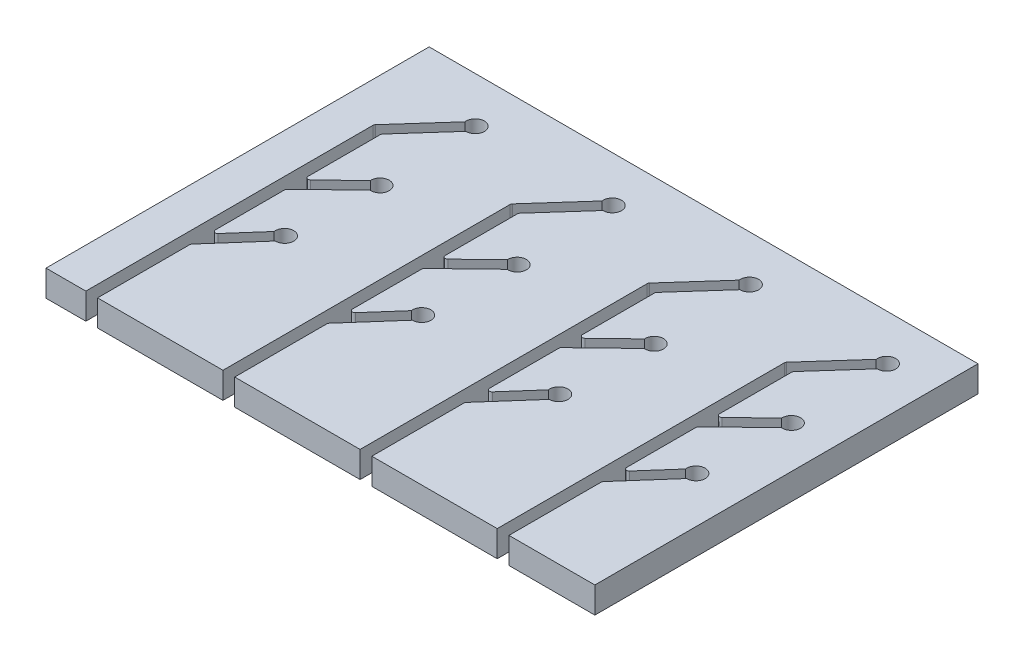
SolidWorks part; units mm, degrees
ref_plane "Front Plane" through (0, 0, 0) normal (0, 0, 1) x (1, 0, 0)
ref_plane "Top Plane" through (0, 0, 0) normal (0, 1, 0) x (1, 0, 0)
ref_plane "Right Plane" through (0, 0, 0) normal (1, 0, 0) x (0, 0, -1)
ref_plane "Plane1" through (0, 10, 0) normal (0, 1, 0) x (1, 0, 0)
sketch "Sketch1" plane through (0, 10, 0) normal (0, 1, 0) x (1, 0, 0)
  line L0 (-60.6438, -106.3471) -> (-60.6438, -33.3849) construction
  line L1 (-95.6438, 187.0307) -> (324.624, 187.0307)
  line L2 (-95.6438, 187.0307) -> (-95.6438, -106.3471)
  line L3 (-95.6438, -106.3471) -> (324.624, -106.3471)
  line L4 (324.624, 187.0307) -> (324.624, -106.3471)
  line L5 (-60.6438, -33.3849) -> (-25.6438, 6.3439) construction
  line L6 (-60.6438, -33.3849) -> (-60.6438, 39.5772) construction
  line L7 (-60.6438, 39.5772) -> (-22.544, 76.3439) construction
  line L8 (-60.6438, 39.5772) -> (-60.6438, 112.5394) construction
  line L9 (-60.6438, 112.5394) -> (-25.376, 152.0307) construction
  line L10 (-25.6438, 6.3439) -> (-60.6438, 6.3439) construction
  line L11 (-56.1438, 54.8828) -> (-56.1438, 110.0594)
  line L12 (-55.6355, 111.3916) -> (-22.0196, 149.0333)
  line L13 (-55.5326, 38.256) -> (-19.4192, 73.1058)
  line L14 (-56.1438, -16.1737) -> (-56.1438, 36.8168)
  line L15 (-55.6445, -34.5176) -> (-22.2672, 3.3693)
  line L16 (-56.1438, -106.3471) -> (-56.1438, -35.8397)
  line L17 (-65.1438, 39.5772) -> (-65.1438, 113.4932)
  line L18 (-64.6355, 114.8254) -> (-28.7324, 155.0282)
  line L19 (-52.7549, 53.4436) -> (-25.6688, 79.5821)
  line L20 (-65.1438, -33.3849) -> (-65.1438, 39.5772)
  line L21 (-52.6431, -17.4958) -> (-29.0203, 9.3186)
  line L22 (-65.1438, -106.3471) -> (-65.1438, -33.3849)
  line L35 (49.3645, 111.3916) -> (82.9804, 149.0333)
  line L36 (40.3645, 114.8254) -> (76.2676, 155.0282)
  line L37 (48.8562, 54.8828) -> (48.8562, 110.0594)
  line L38 (39.8562, 39.5772) -> (39.8562, 113.4932)
  line L39 (52.2451, 53.4436) -> (79.3312, 79.5821)
  line L40 (49.4674, 38.256) -> (85.5808, 73.1058)
  line L41 (48.8562, -16.1737) -> (48.8562, 36.8168)
  line L54 (39.8562, -33.3849) -> (39.8562, 39.5772)
  line L55 (49.3555, -34.5176) -> (82.7328, 3.3693)
  line L56 (52.3569, -17.4958) -> (75.9797, 9.3186)
  line L57 (48.8562, -106.3471) -> (48.8562, -35.8397)
  line L58 (39.8562, -106.3471) -> (39.8562, -33.3849)
  line L59 (154.3645, 111.3916) -> (187.9804, 149.0333)
  line L60 (145.3645, 114.8254) -> (181.2676, 155.0282)
  line L73 (153.8562, 54.8828) -> (153.8562, 110.0594)
  line L74 (144.8562, 39.5772) -> (144.8562, 113.4932)
  line L75 (157.2451, 53.4436) -> (184.3312, 79.5821)
  line L76 (154.4674, 38.256) -> (190.5808, 73.1058)
  line L77 (153.8562, -16.1737) -> (153.8562, 36.8168)
  line L78 (144.8562, -33.3849) -> (144.8562, 39.5772)
  line L79 (154.3555, -34.5176) -> (187.7328, 3.3693)
  line L80 (-57.5189, 36.3391) -> (-19.4192, 73.1058) construction
  line L81 (-56.1438, -33.3849) -> (-56.1438, 39.5772) construction
  line L82 (-56.1438, -106.3471) -> (-56.1438, -33.3849) construction
  line L83 (-57.2672, -36.3596) -> (-22.2672, 3.3693) construction
  line L84 (-64.0203, -30.4102) -> (-29.0203, 9.3186) construction
  line L85 (-63.7686, 42.8153) -> (-25.6688, 79.5821) construction
  line L86 (-56.1438, 39.5772) -> (-56.1438, 110.8225) construction
  line L87 (-65.1438, 39.5772) -> (-65.1438, 114.2562) construction
  line L88 (-65.1438, 114.2562) -> (-28.7324, 155.0282) construction
  line L89 (-56.1438, 110.8225) -> (-22.0196, 149.0333) construction
  line L90 (157.3569, -17.4958) -> (180.9797, 9.3186)
  line L91 (153.8562, -106.3471) -> (153.8562, -35.8397)
  line L92 (144.8562, -106.3471) -> (144.8562, -33.3849)
  line L93 (259.3645, 111.3916) -> (292.9804, 149.0333)
  line L94 (250.3645, 114.8254) -> (286.2676, 155.0282)
  line L95 (258.8562, 54.8828) -> (258.8562, 110.0594)
  line L96 (249.8562, 39.5772) -> (249.8562, 113.4932)
  line L97 (262.2451, 53.4436) -> (289.3312, 79.5821)
  line L98 (259.4674, 38.256) -> (295.5808, 73.1058)
  line L99 (258.8562, -16.1737) -> (258.8562, 36.8168)
  line L100 (249.8562, -33.3849) -> (249.8562, 39.5772)
  line L101 (259.3555, -34.5176) -> (292.7328, 3.3693)
  line L102 (262.3569, -17.4958) -> (285.9797, 9.3186)
  line L103 (258.8562, -106.3471) -> (258.8562, -35.8397)
  line L104 (249.8562, -106.3471) -> (249.8562, -33.3849)
  arc A0 (-56.1438, 39.5772) -> (-65.1438, 39.5772) centre (-60.6438, 39.5772) cw
  arc A1 (-22.0196, 149.0333) -> (-28.7324, 155.0282) centre (-25.376, 152.0307) ccw
  arc A2 (-57.5189, 36.3391) -> (-63.7686, 42.8153) centre (-60.6438, 39.5772) cw
  arc A3 (-19.4192, 73.1058) -> (-25.6688, 79.5821) centre (-22.544, 76.3439) ccw
  arc A4 (-56.1438, -33.3849) -> (-65.1438, -33.3849) centre (-60.6438, -33.3849) cw
  arc A5 (-56.1438, 39.5772) -> (-65.1438, 39.5772) centre (-60.6438, 39.5772) ccw
  arc A6 (-57.2672, -36.3596) -> (-64.0203, -30.4102) centre (-60.6438, -33.3849) cw
  arc A7 (-22.2672, 3.3693) -> (-29.0203, 9.3186) centre (-25.6438, 6.3439) ccw
  arc A8 (-56.1438, -106.3471) -> (-65.1438, -106.3471) centre (-60.6438, -106.3471) cw
  arc A9 (-56.1438, -33.3849) -> (-65.1438, -33.3849) centre (-60.6438, -33.3849) ccw
  circle A10 centre (-25.376, 152.0307) radius 7
  circle A11 centre (-22.544, 76.3439) radius 7
  circle A12 centre (-25.6438, 6.3439) radius 7
  arc A52 (-55.5326, 38.256) -> (-56.1438, 36.8168) centre (-54.1438, 36.8168) ccw
  arc A53 (-56.1438, -35.8397) -> (-55.6445, -34.5176) centre (-54.1438, -35.8397) cw
  arc A54 (-56.1438, -16.1737) -> (-52.6431, -17.4958) centre (-54.1438, -16.1737) ccw
  arc A55 (-52.7549, 53.4436) -> (-56.1438, 54.8828) centre (-54.1438, 54.8828) cw
  arc A56 (-65.1438, 113.4932) -> (-64.6355, 114.8254) centre (-63.1438, 113.4932) cw
  arc A57 (-56.1438, 110.0594) -> (-55.6355, 111.3916) centre (-54.1438, 110.0594) cw
  circle A58 centre (79.624, 152.0307) radius 7
  arc A59 (48.8562, 110.0594) -> (49.3645, 111.3916) centre (50.8562, 110.0594) cw
  arc A60 (39.8562, 113.4932) -> (40.3645, 114.8254) centre (41.8562, 113.4932) cw
  arc A61 (52.2451, 53.4436) -> (48.8562, 54.8828) centre (50.8562, 54.8828) cw
  circle A62 centre (82.456, 76.3439) radius 7
  arc A63 (49.4674, 38.256) -> (48.8562, 36.8168) centre (50.8562, 36.8168) ccw
  circle A64 centre (79.3562, 6.3439) radius 7
  arc A65 (48.8562, -16.1737) -> (52.3569, -17.4958) centre (50.8562, -16.1737) ccw
  arc A66 (48.8562, -35.8397) -> (49.3555, -34.5176) centre (50.8562, -35.8397) cw
  circle A67 centre (184.624, 152.0307) radius 7
  arc A68 (153.8562, 110.0594) -> (154.3645, 111.3916) centre (155.8562, 110.0594) cw
  arc A69 (144.8562, 113.4932) -> (145.3645, 114.8254) centre (146.8562, 113.4932) cw
  arc A70 (157.2451, 53.4436) -> (153.8562, 54.8828) centre (155.8562, 54.8828) cw
  circle A71 centre (187.456, 76.3439) radius 7
  arc A72 (154.4674, 38.256) -> (153.8562, 36.8168) centre (155.8562, 36.8168) ccw
  circle A73 centre (184.3562, 6.3439) radius 7
  arc A74 (153.8562, -16.1737) -> (157.3569, -17.4958) centre (155.8562, -16.1737) ccw
  arc A75 (153.8562, -35.8397) -> (154.3555, -34.5176) centre (155.8562, -35.8397) cw
  circle A76 centre (289.624, 152.0307) radius 7
  arc A77 (258.8562, 110.0594) -> (259.3645, 111.3916) centre (260.8562, 110.0594) cw
  arc A78 (249.8562, 113.4932) -> (250.3645, 114.8254) centre (251.8562, 113.4932) cw
  arc A79 (262.2451, 53.4436) -> (258.8562, 54.8828) centre (260.8562, 54.8828) cw
  circle A80 centre (292.456, 76.3439) radius 7
  arc A81 (259.4674, 38.256) -> (258.8562, 36.8168) centre (260.8562, 36.8168) ccw
  circle A82 centre (289.3562, 6.3439) radius 7
  arc A83 (258.8562, -16.1737) -> (262.3569, -17.4958) centre (260.8562, -16.1737) ccw
  arc A84 (258.8562, -35.8397) -> (259.3555, -34.5176) centre (260.8562, -35.8397) cw
  dimension "D5" = 14
  dimension "D10" = 2
  dimension "D11" = 420.2677
  dimension "D1" = 70
  dimension "D2" = 35
  dimension "D7" = 35
  dimension "D8" = 35
  dimension "D9" = 35
  dimension "D12" = 293.3778
  dimension "D3" = 4.5
  dimension "D4" = 4.5
  dimension "D6" = 4
extrude "Boss-Extrude1" add sketch "Sketch1" along normal blind 20
